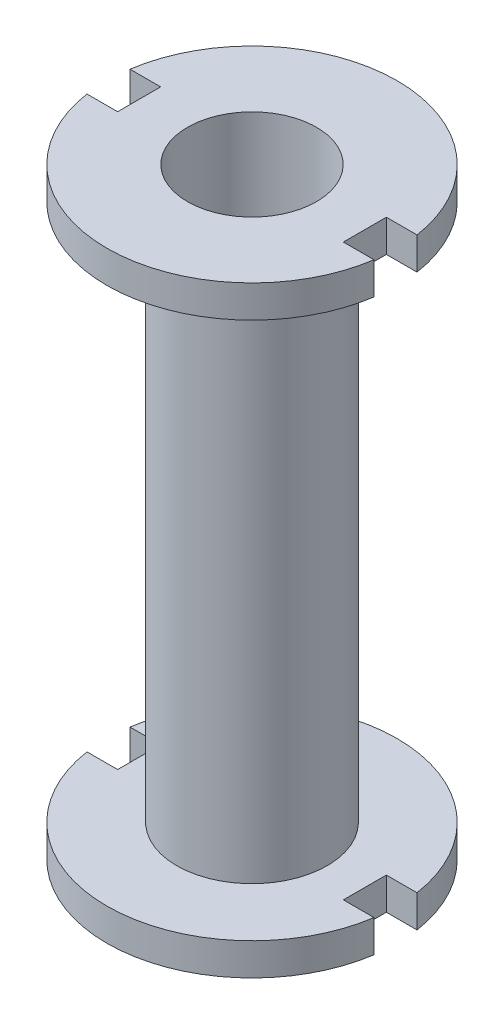
SolidWorks part; units mm, degrees
ref_plane "前视基准面" through (0, 0, 0) normal (0, 0, 1) x (1, 0, 0)
ref_plane "上视基准面" through (0, 0, 0) normal (0, 1, 0) x (1, 0, 0)
ref_plane "右视基准面" through (0, 0, 0) normal (1, 0, 0) x (0, 0, -1)
sketch "草图1" plane through (0, 0, 0) normal (0, 1, 0) x (1, 0, 0)
  circle A0 centre (0, 0) radius 6.75
  circle A1 centre (0, 0) radius 3
  dimension "D1" = 13.5
  dimension "D2" = 6
extrude "凸台-拉伸1" add sketch "草图1" along normal mid plane 28
sketch "草图2" plane through (0, 0, 0) normal (0, 1, 0) x (1, 0, 0)
  circle A0 centre (0, 0) radius 3.5
  circle A1 centre (0, 0) radius 11.3153
  dimension "D1" = 7
extrude "切除-拉伸1" cut sketch "草图2" against normal mid plane 25
sketch "草图4" plane through (0, 14, 0) normal (0, 1, 0) x (1, 0, 0)
  line L1 (-8.25, 1) -> (-5.25, 1)
  line L2 (-8.25, 1) -> (-8.25, -1)
  line L3 (-8.25, -1) -> (-5.25, -1)
  line L4 (-5.25, 1) -> (-5.25, -1)
  line L5 (-8.25, 1) -> (-5.25, -1) construction
  line L6 (-8.25, -1) -> (-5.25, 1) construction
  line L7 (5.25, 1) -> (8.25, 1)
  line L8 (5.25, 1) -> (5.25, -1)
  line L9 (5.25, -1) -> (8.25, -1)
  line L10 (8.25, 1) -> (8.25, -1)
  line L11 (5.25, 1) -> (8.25, -1) construction
  line L12 (5.25, -1) -> (8.25, 1) construction
  circle A0 centre (0, 0) radius 6.75 construction
  circle A1 centre (0, 0) radius 6.75 construction
  point P0 (-6.75, 0)
  point P9 (6.75, 0)
  dimension "D1" = 2
  dimension "D2" = 2
  dimension "D3" = 3
  dimension "D4" = 3
extrude "切除-拉伸2" cut sketch "草图4" against normal through all
